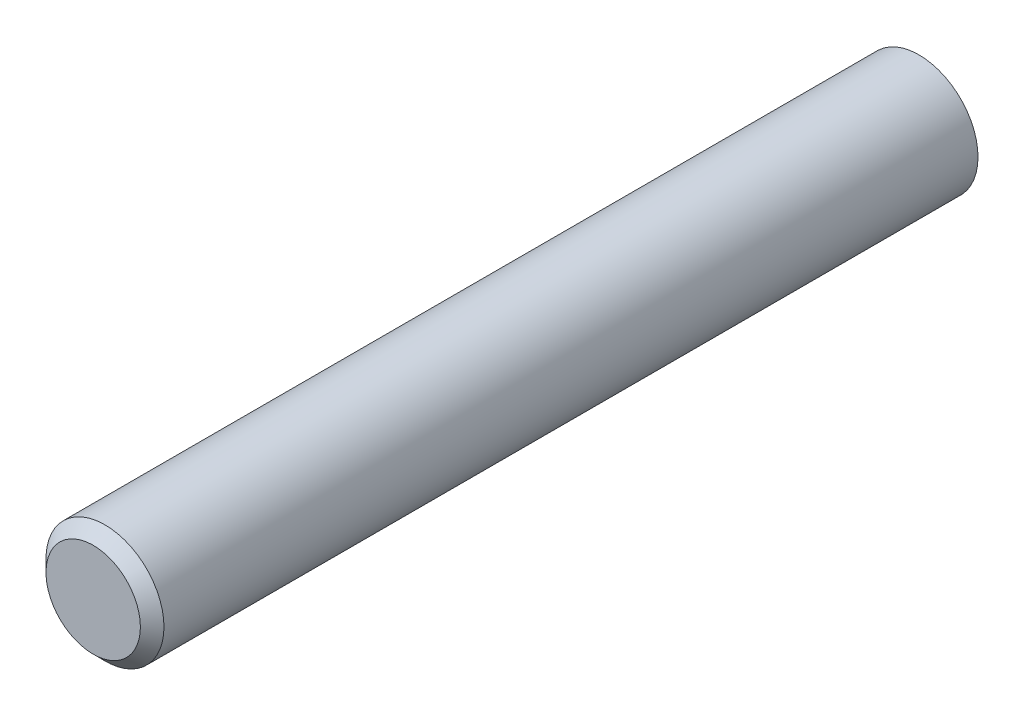
SolidWorks part; units mm, degrees
ref_plane "Front" through (0, 0, 0) normal (0, 0, 1) x (1, 0, 0)
ref_plane "Top" through (0, 0, 0) normal (0, 1, 0) x (1, 0, 0)
ref_plane "Right" through (0, 0, 0) normal (1, 0, 0) x (0, 0, -1)
sketch "Esquisse1" plane through (0, 0, 0) normal (0, 0, 1) x (1, 0, 0)
  circle A0 centre (0, 0) radius 5
  dimension "D1" = 10
extrude "Boss.-Extru.1" add sketch "Esquisse1" along normal blind 70
chamfer "Chanfrein2" distance 1 angle 45 1 edges at (5, 0, 70)
